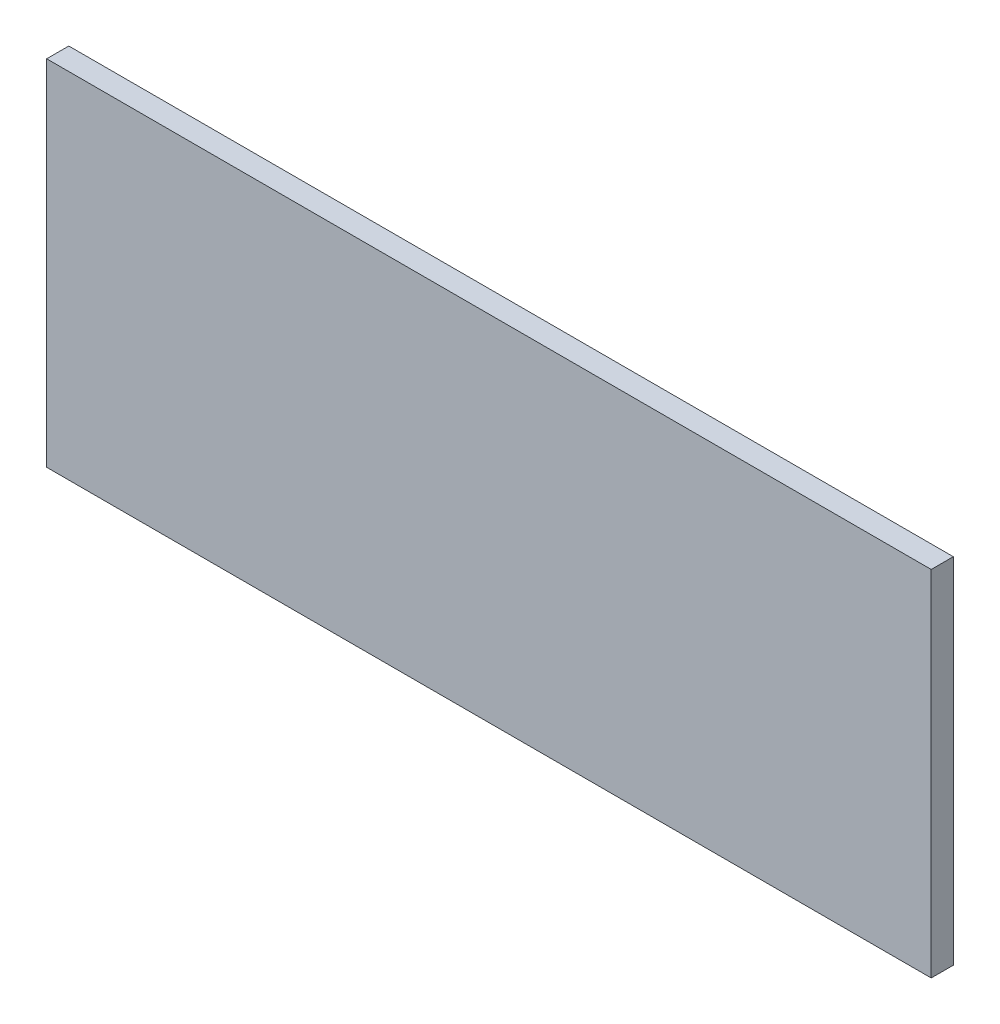
SolidWorks part; units mm, degrees
ref_plane "Front Plane" through (0, 0, 0) normal (0, 0, 1) x (1, 0, 0)
ref_plane "Top Plane" through (0, 0, 0) normal (0, 1, 0) x (1, 0, 0)
ref_plane "Right Plane" through (0, 0, 0) normal (1, 0, 0) x (0, 0, -1)
sketch "Sketch3" plane through (0, 0, 0) normal (0, 0, 1) x (1, 0, 0)
  line L1 (0, 0) -> (-200, 0)
  line L2 (0, 0) -> (0, 80)
  line L3 (0, 80) -> (-200, 80)
  line L4 (-200, 0) -> (-200, 80)
  dimension "D1" = 200
  dimension "D2" = 80
extrude "Boss-Extrude1" add sketch "Sketch3" along normal blind 5
